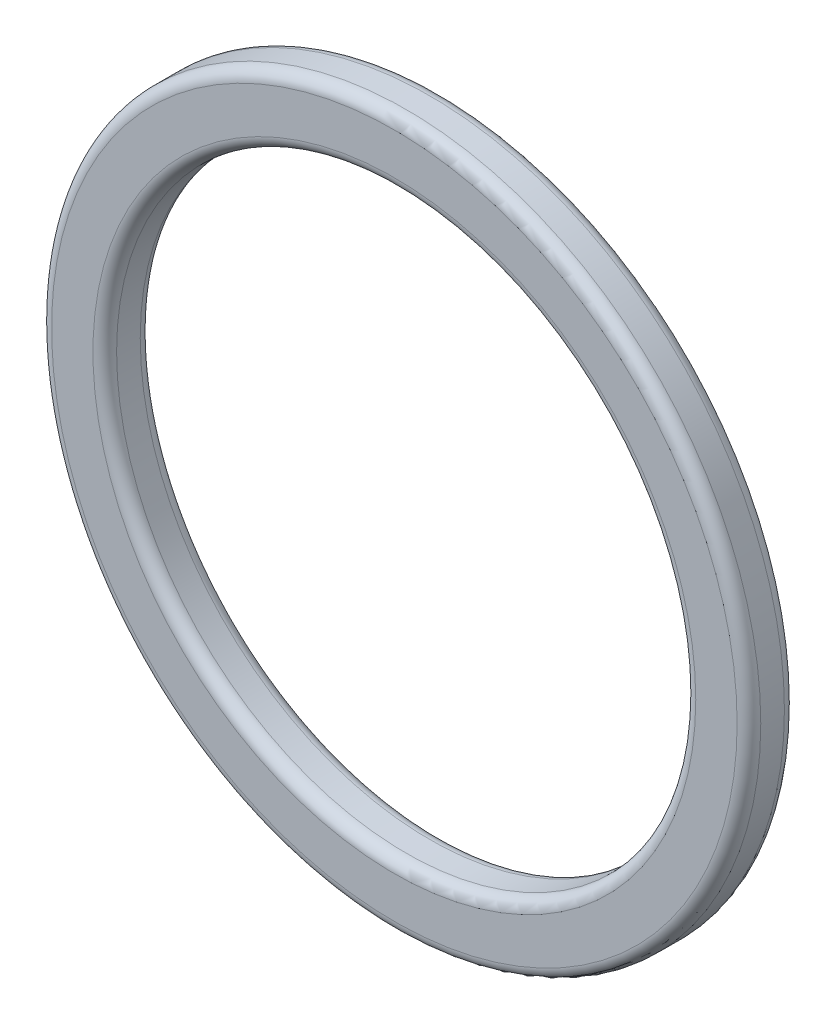
SolidWorks part; units mm, degrees
ref_plane "Front Plane" through (0, 0, 0) normal (0, 0, 1) x (1, 0, 0)
ref_plane "Top Plane" through (0, 0, 0) normal (0, 1, 0) x (1, 0, 0)
ref_plane "Right Plane" through (0, 0, 0) normal (1, 0, 0) x (0, 0, -1)
sketch "Sketch1" plane through (0, 0, 0) normal (0, 0, 1) x (1, 0, 0)
  circle A0 centre (0, 0) radius 12.25
  circle A1 centre (0, 0) radius 15
  dimension "D1" = 24.5
  dimension "D2" = 30
extrude "Boss-Extrude1" add sketch "Sketch1" along normal blind 2
fillet "Fillet1" radius 0.5 2 edges at (12.25, 0, 2) (15, 0, 2)
fillet "Fillet2" radius 0.5 1 edges at (15, 0, 0)
fillet "Fillet3" radius 0.5 1 edges at (12.25, 0, 0)
